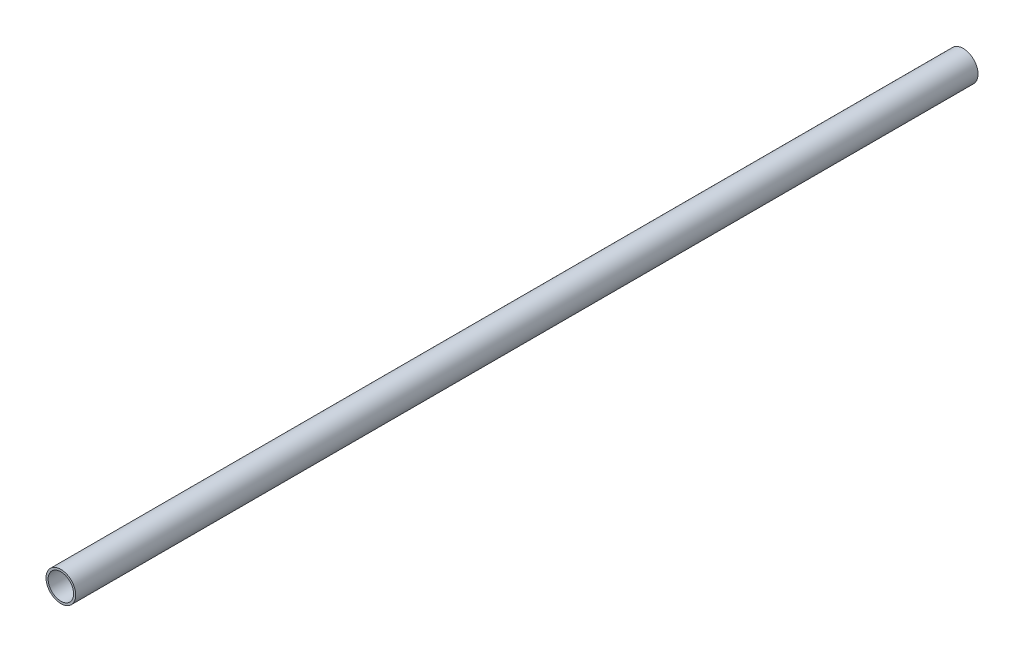
SolidWorks part; units mm, degrees
material "Wing CF"
ref_plane "Front Plane" through (0, 0, 0) normal (0, 0, 1) x (1, 0, 0)
ref_plane "Top Plane" through (0, 0, 0) normal (0, 1, 0) x (1, 0, 0)
ref_plane "Right Plane" through (0, 0, 0) normal (1, 0, 0) x (0, 0, -1)
sketch "Sketch1" plane through (0, 0, 0) normal (0, 0, 1) x (1, 0, 0)
  circle A0 centre (0, 0) radius 7
  circle A1 centre (0, 0) radius 6
  dimension "D1" = 14
  dimension "D2" = 12
extrude "Boss-Extrude1" add sketch "Sketch1" along normal blind 424.86
